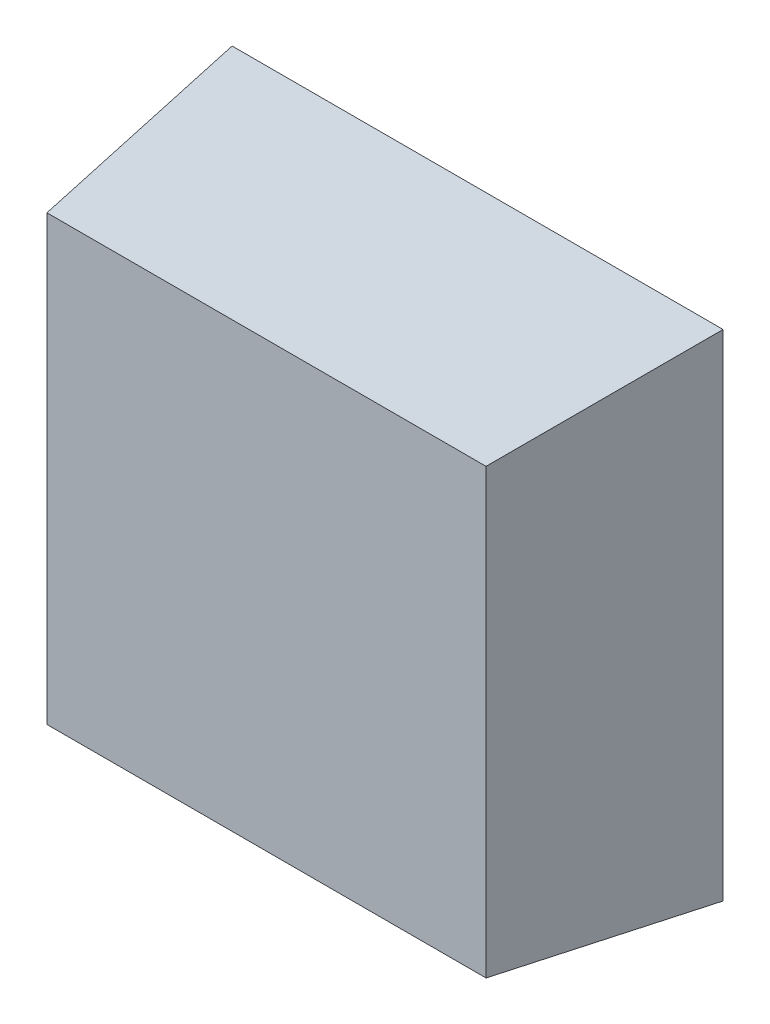
SolidWorks part; units mm, degrees
ref_plane "Front Plane" through (0, 0, 0) normal (0, 0, 1) x (1, 0, 0)
ref_plane "Top Plane" through (0, 0, 0) normal (0, 1, 0) x (1, 0, 0)
ref_plane "Right Plane" through (0, 0, 0) normal (1, 0, 0) x (0, 0, -1)
sketch "Sketch1" plane through (0, 0, 0) normal (0, 0, 1) x (1, 0, 0)
  line L1 (-40.5926, 60.4093) -> (33.1074, 60.4093)
  line L2 (-40.5926, 60.4093) -> (-40.5926, -13.8907)
  line L3 (-40.5926, -13.8907) -> (33.1074, -13.8907)
  line L4 (33.1074, 60.4093) -> (33.1074, -13.8907)
  dimension "D1" = 73.7
  dimension "D2" = 74.3
extrude "Boss-Extrude1" add sketch "Sketch1" along normal blind 31.69 draft 7
sketch "Sketch2" plane through (-39.9897, 0, 4.9101) normal (-0.9925, 0, 0.1219) x (0.1219, 0, 0.9925)
  circle A0 centre (-2.0037, 35.1253) radius 1.5
  dimension "D1" = 3
extrude "Boss-Extrude2" add sketch "Sketch2" along normal blind 10
sketch "Sketch3" plane through (-39.9897, 0, 4.9101) normal (-0.9925, 0, 0.1219) x (0.1219, 0, 0.9925)
  circle A0 centre (-2.0791, 29.5708) radius 1.5
  dimension "D1" = 3
extrude "Boss-Extrude3" add sketch "Sketch3" along normal blind 10
sketch "Sketch4" plane through (-39.9897, 0, 4.9101) normal (-0.9925, 0, 0.1219) x (0.1219, 0, 0.9925)
  circle A0 centre (-2.0883, 24.6766) radius 1.5
  dimension "D1" = 3
extrude "Boss-Extrude4" add sketch "Sketch4" along normal blind 10
sketch "Sketch5" plane through (-39.9897, 0, 4.9101) normal (-0.9925, 0, 0.1219) x (0.1219, 0, 0.9925)
  circle A0 centre (-2.246, 20.1348) radius 1.5
  dimension "D1" = 3
extrude "Boss-Extrude5" add sketch "Sketch5" along normal blind 10 contours A0
